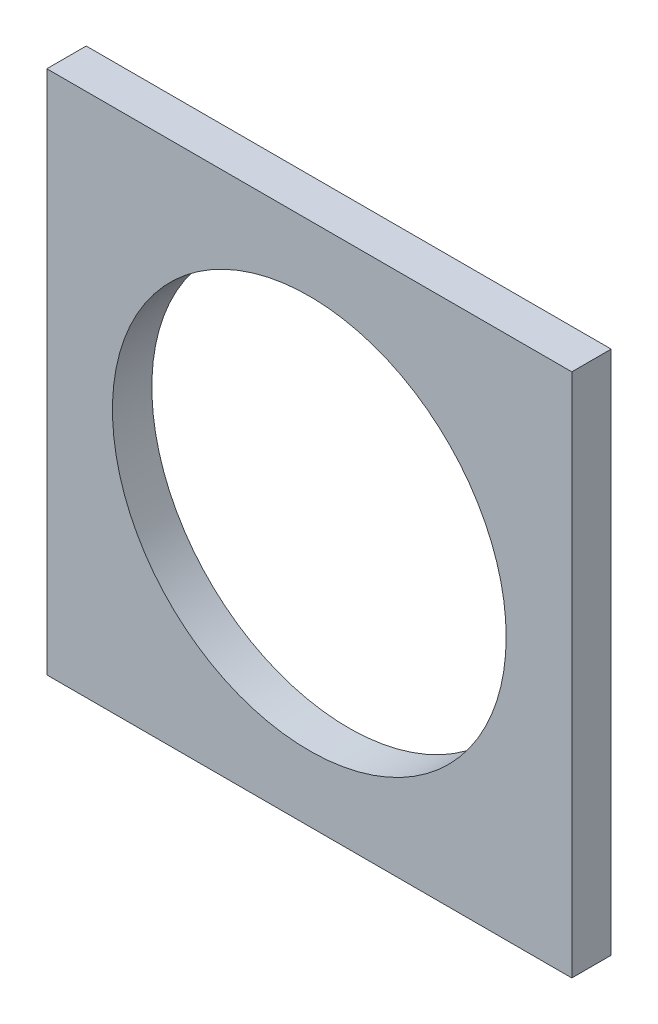
SolidWorks part; units mm, degrees
ref_plane "Alzado" through (0, 0, 0) normal (0, 0, 1) x (1, 0, 0)
ref_plane "Planta" through (0, 0, 0) normal (0, 1, 0) x (1, 0, 0)
ref_plane "Vista lateral" through (0, 0, 0) normal (1, 0, 0) x (0, 0, -1)
sketch "Croquis1" plane through (0, 0, 0) normal (0, 0, 1) x (1, 0, 0)
  line L1 (-20, -20) -> (20, -20)
  line L2 (-20, -20) -> (-20, 20)
  line L3 (-20, 20) -> (20, 20)
  line L4 (20, -20) -> (20, 20)
  line L5 (-20, -20) -> (20, 20) construction
  line L6 (-20, 20) -> (20, -20) construction
  circle A0 centre (0, 0) radius 15
  dimension "D3" = 30
  dimension "D1" = 40
  dimension "D2" = 40
extrude "Saliente-Extruir1" add sketch "Croquis1" along normal blind 3
